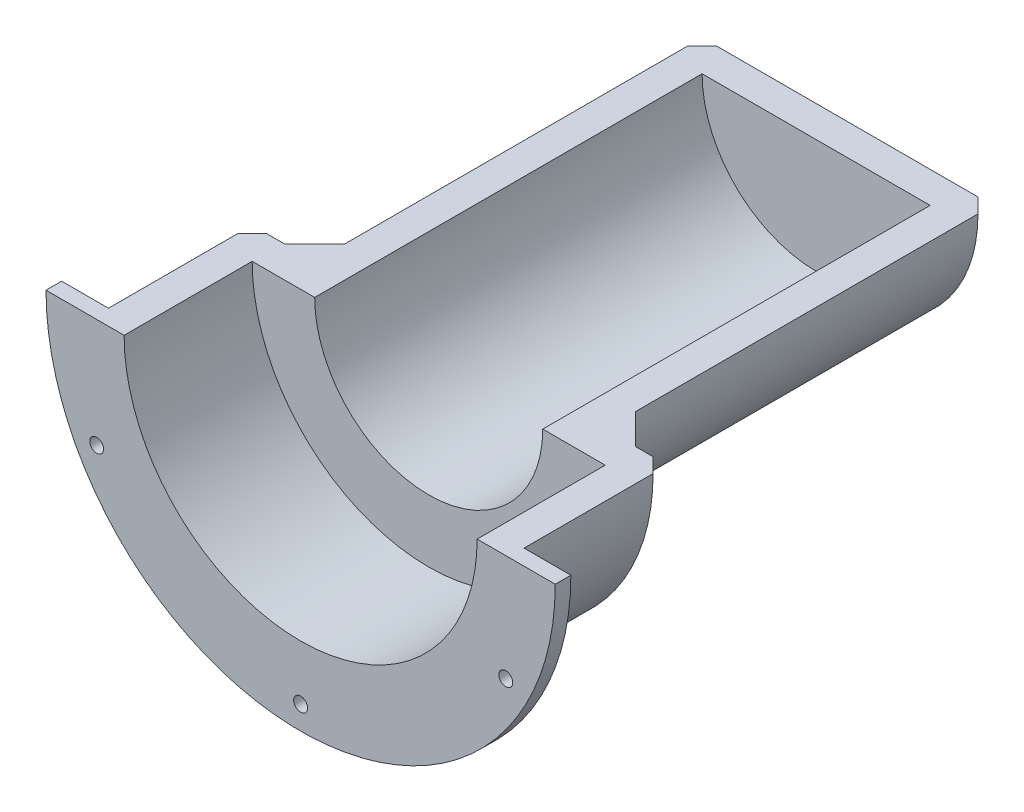
SolidWorks part; units mm, degrees
ref_plane "Front Plane" through (0, 0, 0) normal (0, 0, 1) x (1, 0, 0)
ref_plane "Top Plane" through (0, 0, 0) normal (0, 1, 0) x (1, 0, 0)
ref_plane "Right Plane" through (0, 0, 0) normal (1, 0, 0) x (0, 0, -1)
sketch "Sketch2" plane through (0, 0, 0) normal (0, 0, 1) x (1, 0, 0)
  line L0 (-23.622, 0) -> (23.622, 0) construction
  line L1 (-23.622, 0) -> (23.622, 0)
  arc A0 (-23.622, 0) -> (23.622, 0) centre (0, 0) ccw
  arc A1 (-18.542, 0) -> (18.542, 0) centre (0, 0) ccw
  arc A2 (18.542, 0) -> (-18.542, 0) centre (0, 0) ccw construction
  arc A3 (23.622, 0) -> (-23.622, 0) centre (0, 0) ccw construction
  dimension "D1" = 47.244
extrude "Boss-Extrude1" add sketch "Sketch2" against normal blind 62.992 contours A1 L1 A0
sketch "Sketch3" plane through (0, 0, 0) normal (0, 0, 1) x (1, 0, 0)
  line L0 (-23.622, 0) -> (23.622, 0) construction
  line L1 (-18.542, 0) -> (18.542, 0)
  arc A0 (-18.542, 0) -> (18.542, 0) centre (0, 0) ccw
extrude "Cut-Extrude1" cut sketch "Sketch3" against normal blind 57.912
sketch "Sketch5" plane through (0, 0, 0) normal (0, 0, 1) x (1, 0, 0)
  line L0 (-33.782, 0) -> (33.782, 0)
  arc A0 (-33.782, 0) -> (33.782, 0) centre (0, 0) ccw
extrude "Boss-Extrude2" add sketch "Sketch5" along normal blind 25.908
sketch "Sketch6" plane through (0, 0, 25.908) normal (0, 0, 1) x (1, 0, 0)
  line L0 (33.782, 0) -> (-33.782, 0) construction
  line L1 (-18.542, 0) -> (18.542, 0)
  arc A0 (-18.542, 0) -> (18.542, 0) centre (0, 0) ccw
extrude "Cut-Extrude2" cut sketch "Sketch6" against normal blind 25.908
sketch "Sketch7" plane through (0, 0, 25.908) normal (0, 0, 1) x (1, 0, 0)
  line L0 (-18.542, 0) -> (-33.782, 0) construction
  line L1 (33.782, 0) -> (18.542, 0) construction
  line L2 (-28.702, 0) -> (28.702, 0)
  arc A0 (-28.702, 0) -> (28.702, 0) centre (0, 0) ccw
extrude "Cut-Extrude3" cut sketch "Sketch7" against normal blind 20.828
sketch "Sketch9" plane through (0, 0, 25.908) normal (0, 0, 1) x (1, 0, 0)
  line L0 (-41.402, 0) -> (41.402, 0)
  arc A0 (-41.402, 0) -> (41.402, 0) centre (0, 0) ccw
extrude "Boss-Extrude3" add sketch "Sketch9" against normal blind 2.54
sketch "Sketch10" plane through (0, 0, 25.908) normal (0, 0, 1) x (1, 0, 0)
  line L0 (41.402, 0) -> (-41.402, 0) construction
  line L1 (-28.702, 0) -> (28.702, 0)
  arc A0 (-28.702, 0) -> (28.702, 0) centre (0, 0) ccw
extrude "Cut-Extrude4" cut sketch "Sketch10" against normal blind 2.54
chamfer "Chamfer1" distance 4.92 angle 45 1 edges at (0, -23.622, 0)
chamfer "Chamfer3" distance 2.38 angle 45 1 edges at (0, -23.622, -62.992)
chamfer "Chamfer4" distance 2.38 angle 45 1 edges at (0, -33.782, 0)
sketch "Sketch12" plane through (0, 0, 23.368) normal (0, 0, -1) x (-1, 0, 0)
  circle A0 centre (0, -37.592) radius 1.1303
  arc A2 (-33.782, 0) -> (33.782, 0) centre (0, 0) ccw construction
  point P12 (0, -33.782)
  dimension "D1" = 3.81
  dimension "D2" = 2.2606
extrude "Cut-Extrude6" cut sketch "Sketch12" against normal blind 2.54
sketch "Sketch16" plane through (0, 0, 25.908) normal (0, 0, 1) x (1, 0, 0)
  circle A0 centre (-33.1564, -17.7147) radius 1.1303
  circle A1 centre (33.3594, -17.3294) radius 1.1303
  arc A2 (-41.402, 0) -> (41.402, 0) centre (0, 0) ccw construction
  dimension "D1" = 37.592
  dimension "D3" = 2.2606
  dimension "D4" = 2.2606
  dimension "D2" = 37.592
extrude "Cut-Extrude7" cut sketch "Sketch16" against normal blind 2.54
